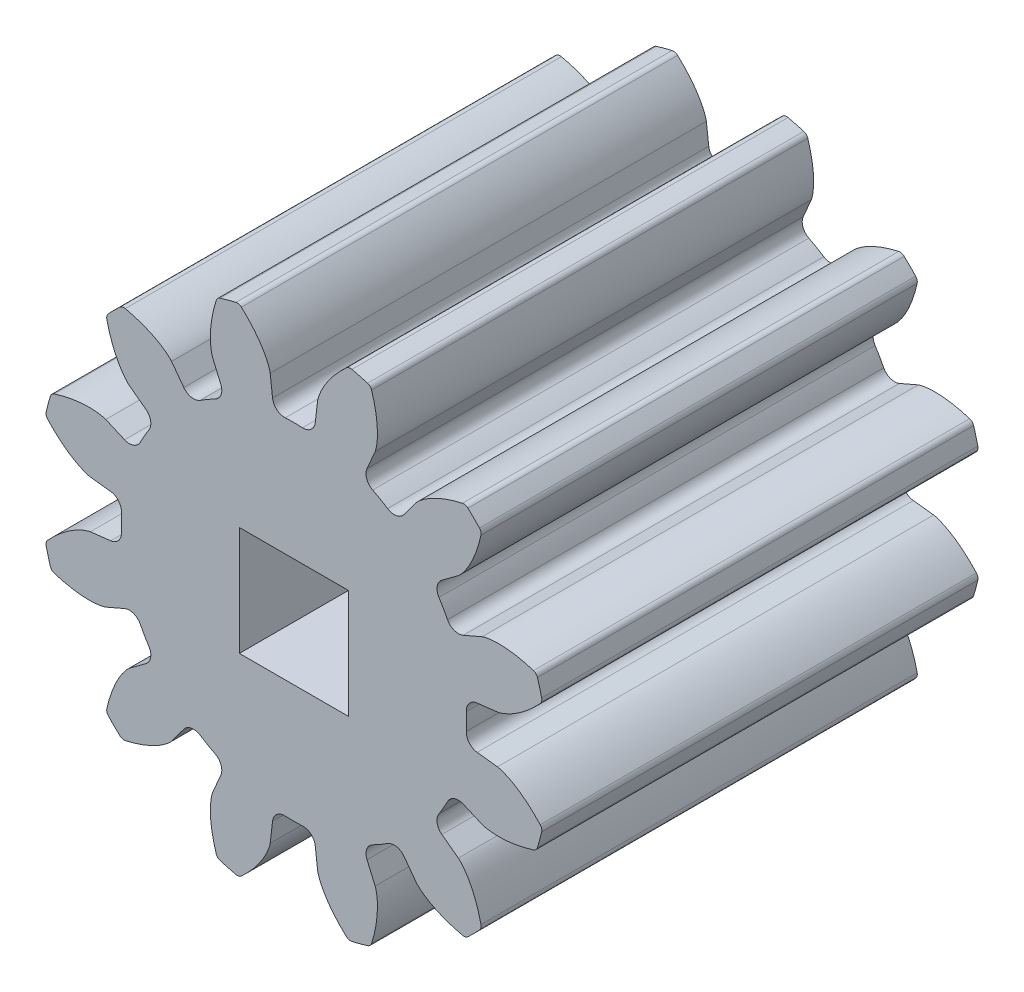
SolidWorks part; units mm, degrees
material "ABS"
ref_plane "Front" through (0, 0, 0) normal (0, 0, 1) x (1, 0, 0)
ref_plane "Top" through (0, 0, 0) normal (0, 1, 0) x (1, 0, 0)
ref_plane "Right" through (0, 0, 0) normal (1, 0, 0) x (0, 0, -1)
sketch "Sketch1" plane through (0, 0, 0) normal (0, 0, 1) x (1, 0, 0)
  circle A0 centre (0, 0) radius 7.4083
extrude "Boss-Extrude1" add sketch "Sketch1" along normal blind 12.7
sketch "Sketch3" plane through (0, 0, 0) normal (0, 0, 1) x (1, 0, 0)
  line L0 (0, 0) -> (43.7181, 0) construction
  line L2 (0, 0) -> (-0.5818, 4.9933) construction
  line L3 (0, 0) -> (0.5818, 4.9933) construction
  line L4 (0.5818, 4.9933) -> (0.6906, 5.927) construction
  line L5 (0, 0) -> (0, 61.276) construction
  line L6 (-0.5818, 4.9933) -> (-0.6906, 5.927) construction
  circle A0 centre (0, 0) radius 7.4083 construction
  circle A1 centre (0, 0) radius 6.35 construction
  circle A2 centre (0, 0) radius 5.967 construction
  arc A3 (0.5818, 4.9933) -> (-0.5818, 4.9933) centre (0, 0) ccw construction
  arc A5 (1.5983, 7.2339) -> (-1.5983, 7.2339) centre (0, 0) ccw
  spline S0 degree 4 poles (-0.6906, 5.927) (-0.6909, 5.9293) (-0.6919, 5.9359) (-0.6942, 5.9484) (-0.6987, 5.9686) (-0.7052, 5.9942) (-0.7148, 6.0271) (-0.7275, 6.0655) (-0.7428, 6.1073) (-0.761, 6.1523) (-0.7804, 6.1969) (-0.8011, 6.2409) (-0.8228, 6.2844) (-0.8503, 6.3367) (-0.8852, 6.3986) (-0.9285, 6.47) (-0.9807, 6.5497) (-1.0371, 6.6294) (-1.0952, 6.7066) (-1.1568, 6.7832) (-1.2185, 6.8562) (-1.2856, 6.9304) (-1.3489, 6.9981) (-1.4232, 7.0721) (-1.484, 7.1312) (-1.5675, 7.2071) (-1.6179, 7.2513) (-1.6779, 7.3023) (-1.7051, 7.3245) (-1.7219, 7.3382) knots 0 0 0 0 0 0.005377 0.015084 0.028532 0.04661 0.064855 0.092111 0.119476 0.146842 0.174209 0.201575 0.228941 0.256307 0.307035 0.361767 0.4165 0.471232 0.525964 0.580697 0.635429 0.690161 0.744894 0.799626 0.854358 0.909091 0.954545 1 1 1 1 1 construction
  spline S1 degree 4 poles (-0.6906, 5.927) (-0.6909, 5.9293) (-0.6919, 5.9359) (-0.6942, 5.9484) (-0.6987, 5.9686) (-0.7052, 5.9942) (-0.7148, 6.0271) (-0.7275, 6.0655) (-0.7428, 6.1073) (-0.761, 6.1523) (-0.7804, 6.1969) (-0.8011, 6.2409) (-0.8228, 6.2844) (-0.8503, 6.3367) (-0.8852, 6.3986) (-0.9285, 6.47) (-0.9807, 6.5497) (-1.0371, 6.6294) (-1.0952, 6.7066) (-1.1568, 6.7832) (-1.2185, 6.8562) (-1.2856, 6.9304) (-1.3489, 6.9981) (-1.4232, 7.0721) (-1.484, 7.1312) (-1.5494, 7.1906) (-1.5816, 7.2193) (-1.5983, 7.2339) knots 0 0 0 0 0 0.005377 0.015084 0.028532 0.04661 0.064855 0.092111 0.119476 0.146842 0.174209 0.201575 0.228941 0.256307 0.307035 0.361767 0.4165 0.471232 0.525964 0.580697 0.635429 0.690161 0.744894 0.799626 0.854358 0.909091 0.909091 0.909091 0.909091 0.909091
  spline S2 degree 4 poles (0.6906, 5.927) (0.6909, 5.9293) (0.6919, 5.9359) (0.6942, 5.9484) (0.6987, 5.9686) (0.7052, 5.9942) (0.7148, 6.0271) (0.7275, 6.0655) (0.7428, 6.1073) (0.761, 6.1523) (0.7804, 6.1969) (0.8011, 6.2409) (0.8228, 6.2844) (0.8503, 6.3367) (0.8852, 6.3986) (0.9285, 6.47) (0.9807, 6.5497) (1.0371, 6.6294) (1.0952, 6.7066) (1.1568, 6.7832) (1.2185, 6.8562) (1.2856, 6.9304) (1.3489, 6.9981) (1.4232, 7.0721) (1.484, 7.1312) (1.5675, 7.2071) (1.6179, 7.2513) (1.6779, 7.3023) (1.7051, 7.3245) (1.7219, 7.3382) knots 0 0 0 0 0 0.005377 0.015084 0.028532 0.04661 0.064855 0.092111 0.119476 0.146842 0.174209 0.201575 0.228941 0.256307 0.307035 0.361767 0.4165 0.471232 0.525964 0.580697 0.635429 0.690161 0.744894 0.799626 0.854358 0.909091 0.954545 1 1 1 1 1 construction
  spline S3 degree 4 poles (0.6906, 5.927) (0.6909, 5.9293) (0.6919, 5.9359) (0.6942, 5.9484) (0.6987, 5.9686) (0.7052, 5.9942) (0.7148, 6.0271) (0.7275, 6.0655) (0.7428, 6.1073) (0.761, 6.1523) (0.7804, 6.1969) (0.8011, 6.2409) (0.8228, 6.2844) (0.8503, 6.3367) (0.8852, 6.3986) (0.9285, 6.47) (0.9807, 6.5497) (1.0371, 6.6294) (1.0952, 6.7066) (1.1568, 6.7832) (1.2185, 6.8562) (1.2856, 6.9304) (1.3489, 6.9981) (1.4232, 7.0721) (1.484, 7.1312) (1.5494, 7.1906) (1.5816, 7.2193) (1.5983, 7.2339) knots 0 0 0 0 0 0.005377 0.015084 0.028532 0.04661 0.064855 0.092111 0.119476 0.146842 0.174209 0.201575 0.228941 0.256307 0.307035 0.361767 0.4165 0.471232 0.525964 0.580697 0.635429 0.690161 0.744894 0.799626 0.854358 0.909091 0.909091 0.909091 0.909091 0.909091
  point P0 (0, 5.0271)
sketch "DCLTBC" plane through (0, 0, 0) normal (0, 0, 1) x (1, 0, 0)
  line L0 (0, 0) -> (41.04, 0) construction
  line L1 (-0.5818, 4.9933) -> (-0.6906, 5.927) construction
  line L2 (0.5818, 4.9933) -> (0.6906, 5.927) construction
  line L3 (-0.5818, 4.9933) -> (-0.6906, 5.927)
  line L4 (0.5818, 4.9933) -> (0.6906, 5.927)
  line L5 (0, 0) -> (0, 104.9356) construction
  circle A0 centre (0, 0) radius 7.4083
  circle A1 centre (0, 0) radius 6.35 construction
  circle A2 centre (0, 0) radius 5.967 construction
  arc A3 (0.5818, 4.9933) -> (-0.5818, 4.9933) centre (0, 0) ccw construction
  arc A4 (0.5818, 4.9933) -> (-0.5818, 4.9933) centre (0, 0) ccw
  spline S0 degree 4 poles (-992.2327, -123.7493) (-11.7184, 3.7577) (-0.7821, 5.3359) (-0.6334, 5.6707) (-0.6987, 5.9686) (-0.7052, 5.9942) (-0.7148, 6.0271) (-0.7275, 6.0655) (-0.7428, 6.1073) (-0.761, 6.1523) (-0.7804, 6.1969) (-0.8011, 6.2409) (-0.8228, 6.2844) (-0.8503, 6.3367) (-0.8852, 6.3986) (-0.9285, 6.47) (-0.9807, 6.5497) (-1.0371, 6.6294) (-1.0952, 6.7066) (-1.1568, 6.7832) (-1.2185, 6.8562) (-1.2856, 6.9304) (-1.3489, 6.9981) (-1.4232, 7.0721) (-1.7629, 7.4024) (-3.091, 8.4823) (16.0015, -8.3782) (-754.2601, 665.5952) knots -0.639841 -0.639841 -0.639841 -0.639841 -0.639841 0.005377 0.015084 0.028532 0.04661 0.064855 0.092111 0.119476 0.146842 0.174209 0.201575 0.228941 0.256307 0.307035 0.361767 0.4165 0.471232 0.525964 0.580697 0.635429 0.690161 0.744894 0.799626 0.854358 1.913215 1.913215 1.913215 1.913215 1.913215 only from (-0.6906, 5.927) to (-1.5983, 7.2339) construction
  spline S1 degree 4 poles (992.2327, -123.7493) (11.7184, 3.7577) (0.7821, 5.3359) (0.6334, 5.6707) (0.6987, 5.9686) (0.7052, 5.9942) (0.7148, 6.0271) (0.7275, 6.0655) (0.7428, 6.1073) (0.761, 6.1523) (0.7804, 6.1969) (0.8011, 6.2409) (0.8228, 6.2844) (0.8503, 6.3367) (0.8852, 6.3986) (0.9285, 6.47) (0.9807, 6.5497) (1.0371, 6.6294) (1.0952, 6.7066) (1.1568, 6.7832) (1.2185, 6.8562) (1.2856, 6.9304) (1.3489, 6.9981) (1.4232, 7.0721) (1.7629, 7.4024) (3.091, 8.4823) (-16.0015, -8.3782) (754.2601, 665.5952) knots -0.639841 -0.639841 -0.639841 -0.639841 -0.639841 0.005377 0.015084 0.028532 0.04661 0.064855 0.092111 0.119476 0.146842 0.174209 0.201575 0.228941 0.256307 0.307035 0.361767 0.4165 0.471232 0.525964 0.580697 0.635429 0.690161 0.744894 0.799626 0.854358 1.913215 1.913215 1.913215 1.913215 1.913215 only from (0.6906, 5.927) to (1.5983, 7.2339) construction
  spline S2 degree 4 poles (-0.6906, 5.927) (-0.6909, 5.9293) (-0.6919, 5.9359) (-0.6942, 5.9484) (-0.6987, 5.9686) (-0.7052, 5.9942) (-0.7148, 6.0271) (-0.7275, 6.0655) (-0.7428, 6.1073) (-0.761, 6.1523) (-0.7804, 6.1969) (-0.8011, 6.2409) (-0.8228, 6.2844) (-0.8503, 6.3367) (-0.8852, 6.3986) (-0.9285, 6.47) (-0.9807, 6.5497) (-1.0371, 6.6294) (-1.0952, 6.7066) (-1.1568, 6.7832) (-1.2185, 6.8562) (-1.2856, 6.9304) (-1.3489, 6.9981) (-1.4232, 7.0721) (-1.484, 7.1312) (-1.5494, 7.1906) (-1.5816, 7.2193) (-1.5983, 7.2339) knots 0 0 0 0 0 0.005377 0.015084 0.028532 0.04661 0.064855 0.092111 0.119476 0.146842 0.174209 0.201575 0.228941 0.256307 0.307035 0.361767 0.4165 0.471232 0.525964 0.580697 0.635429 0.690161 0.744894 0.799626 0.854358 0.909091 0.909091 0.909091 0.909091 0.909091
  spline S3 degree 4 poles (0.6906, 5.927) (0.6909, 5.9293) (0.6919, 5.9359) (0.6942, 5.9484) (0.6987, 5.9686) (0.7052, 5.9942) (0.7148, 6.0271) (0.7275, 6.0655) (0.7428, 6.1073) (0.761, 6.1523) (0.7804, 6.1969) (0.8011, 6.2409) (0.8228, 6.2844) (0.8503, 6.3367) (0.8852, 6.3986) (0.9285, 6.47) (0.9807, 6.5497) (1.0371, 6.6294) (1.0952, 6.7066) (1.1568, 6.7832) (1.2185, 6.8562) (1.2856, 6.9304) (1.3489, 6.9981) (1.4232, 7.0721) (1.484, 7.1312) (1.5494, 7.1906) (1.5816, 7.2193) (1.5983, 7.2339) knots 0 0 0 0 0 0.005377 0.015084 0.028532 0.04661 0.064855 0.092111 0.119476 0.146842 0.174209 0.201575 0.228941 0.256307 0.307035 0.361767 0.4165 0.471232 0.525964 0.580697 0.635429 0.690161 0.744894 0.799626 0.854358 0.909091 0.909091 0.909091 0.909091 0.909091
extrude "Cut-Extrude-DCLTBC" cut sketch "DCLTBC" along normal through all
fillet "Fillet-Tip-DCLTBC" radius 0.1775 2 edges at (1.5983, 7.2339, 6.35) (-1.5983, 7.2339, 6.35)
fillet "Fillet-Root-DCLTBC" radius 0.3551 2 edges at (-0.5818, 4.9933, 6.35) (0.5818, 4.9933, 6.35)
pattern_circular "CirPattern-DCLTBC" count 12 over 360 about axis through (0, 0, 12.7) along (0, 0, 1) of "Cut-Extrude-DCLTBC", "Fillet-Tip-DCLTBC", "Fillet-Root-DCLTBC"
sketch "DCGTBC" [suppressed] plane through (0, 0, 0) normal (0, 0, 1) x (1, 0, 0)
  line L0 (0, 0) -> (41.04, 0) construction
  line L1 (-33.4742, 2.9286) -> (0, 0) construction
  line L2 (0, 0) -> (33.4742, 2.9286) construction
  line L3 (0, 0) -> (-16.5124, 0)
  line L5 (0, 0) -> (0, 104.9356) construction
  circle A0 centre (0, 0) radius 35.9833
  circle A1 centre (0, 0) radius 34.925 construction
  circle A2 centre (0, 0) radius 32.8188 construction
  arc A3 (0.2989, 33.6008) -> (-0.2989, 33.6008) centre (0, 0) ccw construction
  arc A11 (33.4742, 2.9286) -> (-33.4742, 2.9286) centre (0, 0) ccw
  spline S4 degree 4 poles (999.6179, -3.7707) (12.1623, 31.0827) (0.4581, 31.7209) (0.2553, 32.3127) (0.2967, 32.9045) (0.3017, 32.9586) (0.3095, 33.0284) (0.3204, 33.1106) (0.3343, 33.201) (0.3514, 33.2993) (0.3703, 33.3974) (0.3907, 33.4951) (0.4126, 33.5925) (0.4408, 33.7105) (0.477, 33.8518) (0.523, 34.017) (0.5794, 34.2042) (0.6413, 34.395) (0.706, 34.5826) (0.7756, 34.772) (0.846, 34.9552) (0.9235, 35.1454) (0.9973, 35.3209) (1.0848, 35.5175) (1.4313, 36.2799) (2.6636, 38.6565) (-10.9768, 10.7922) (444.1484, 932.5353) knots -0.603811 -0.603811 -0.603811 -0.603811 -0.603811 0.005377 0.015084 0.028532 0.04661 0.064855 0.092111 0.119476 0.146842 0.174209 0.201575 0.228941 0.256307 0.307035 0.361767 0.4165 0.471232 0.525964 0.580697 0.635429 0.690161 0.744894 0.799626 0.854358 1.742885 1.742885 1.742885 1.742885 1.742885 only from (0.2919, 32.8175) to (1.2943, 35.96) construction
  spline S5 degree 4 poles (-999.6179, -3.7707) (-12.1623, 31.0827) (-0.4581, 31.7209) (-0.2553, 32.3127) (-0.2967, 32.9045) (-0.3017, 32.9586) (-0.3095, 33.0284) (-0.3204, 33.1106) (-0.3343, 33.201) (-0.3514, 33.2993) (-0.3703, 33.3974) (-0.3907, 33.4951) (-0.4126, 33.5925) (-0.4408, 33.7105) (-0.477, 33.8518) (-0.523, 34.017) (-0.5794, 34.2042) (-0.6413, 34.395) (-0.706, 34.5826) (-0.7756, 34.772) (-0.846, 34.9552) (-0.9235, 35.1454) (-0.9973, 35.3209) (-1.0848, 35.5175) (-1.4313, 36.2799) (-2.6636, 38.6565) (10.9768, 10.7922) (-444.1484, 932.5353) knots -0.603811 -0.603811 -0.603811 -0.603811 -0.603811 0.005377 0.015084 0.028532 0.04661 0.064855 0.092111 0.119476 0.146842 0.174209 0.201575 0.228941 0.256307 0.307035 0.361767 0.4165 0.471232 0.525964 0.580697 0.635429 0.690161 0.744894 0.799626 0.854358 1.742885 1.742885 1.742885 1.742885 1.742885 only from (-0.2919, 32.8175) to (-1.2943, 35.96) construction
  spline S6 degree 4 poles (0.2919, 32.8175) (0.292, 32.8224) (0.2924, 32.8361) (0.2937, 32.8621) (0.2967, 32.9045) (0.3017, 32.9586) (0.3095, 33.0284) (0.3204, 33.1106) (0.3343, 33.201) (0.3514, 33.2993) (0.3703, 33.3974) (0.3907, 33.4951) (0.4126, 33.5925) (0.4408, 33.7105) (0.477, 33.8518) (0.523, 34.017) (0.5794, 34.2042) (0.6413, 34.395) (0.706, 34.5826) (0.7756, 34.772) (0.846, 34.9552) (0.9235, 35.1454) (0.9973, 35.3209) (1.0848, 35.5175) (1.1568, 35.676) (1.2354, 35.8397) (1.2742, 35.9193) (1.2943, 35.96) knots 0 0 0 0 0 0.005377 0.015084 0.028532 0.04661 0.064855 0.092111 0.119476 0.146842 0.174209 0.201575 0.228941 0.256307 0.307035 0.361767 0.4165 0.471232 0.525964 0.580697 0.635429 0.690161 0.744894 0.799626 0.854358 0.909091 0.909091 0.909091 0.909091 0.909091
  spline S7 degree 4 poles (-0.2919, 32.8175) (-0.292, 32.8224) (-0.2924, 32.8361) (-0.2937, 32.8621) (-0.2967, 32.9045) (-0.3017, 32.9586) (-0.3095, 33.0284) (-0.3204, 33.1106) (-0.3343, 33.201) (-0.3514, 33.2993) (-0.3703, 33.3974) (-0.3907, 33.4951) (-0.4126, 33.5925) (-0.4408, 33.7105) (-0.477, 33.8518) (-0.523, 34.017) (-0.5794, 34.2042) (-0.6413, 34.395) (-0.706, 34.5826) (-0.7756, 34.772) (-0.846, 34.9552) (-0.9235, 35.1454) (-0.9973, 35.3209) (-1.0848, 35.5175) (-1.1568, 35.676) (-1.2354, 35.8397) (-1.2742, 35.9193) (-1.2943, 35.96) knots 0 0 0 0 0 0.005377 0.015084 0.028532 0.04661 0.064855 0.092111 0.119476 0.146842 0.174209 0.201575 0.228941 0.256307 0.307035 0.361767 0.4165 0.471232 0.525964 0.580697 0.635429 0.690161 0.744894 0.799626 0.854358 0.909091 0.909091 0.909091 0.909091 0.909091
  dimension "D1" = 5
  dimension "D2" = 5
extrude "Cut-Extrude-DCGTBC" [suppressed] cut sketch "DCGTBC" along normal through all
fillet "Fillet-Tip-DCGTBC" [suppressed] radius 0.1775
pattern_circular "CirPattern-DCGTBC" [suppressed] count 12 over 360
sketch "Sketch4" plane through (0, 0, 12.7) normal (0, 0, 1) x (1, 0, 0)
  line L1 (-1.5875, -1.5875) -> (1.5875, -1.5875)
  line L2 (-1.5875, -1.5875) -> (-1.5875, 1.5875)
  line L3 (-1.5875, 1.5875) -> (1.5875, 1.5875)
  line L4 (1.5875, -1.5875) -> (1.5875, 1.5875)
  line L5 (-1.5875, -1.5875) -> (1.5875, 1.5875) construction
  line L6 (-1.5875, 1.5875) -> (1.5875, -1.5875) construction
  point P0 (0, 0)
  dimension "D1" = 3.175
extrude "Cut-Extrude2" cut sketch "Sketch4" against normal through all
equation "\"DiametralPitch\"= 24'Diametral Pitch"
equation "\"NumTeeth\"= 12'Number of Teeth"
equation "\"PressureAngle\"= 20deg'Pressure Angle"
equation "\"Addendum\"= 1 / \"DiametralPitch\"'Addendum"
equation "\"Dedendum\"= 1.25 / \"DiametralPitch\"'Dedendum"
equation "\"WorkingDepth\"= 2 / \"DiametralPitch\"'Working Depth - here for REF (Not used in building model)"
equation "\"WholeDepth\"= 2.25 / \"DiametralPitch\"'Whole Depth - here for REF (Not used in building model)"
equation "\"Clearance\"= .25 / \"DiametralPitch\"'Clearance"
equation "\"CircularPitch\"= pi / \"DiametralPitch\"'Circular Pitch - here for REF (Not used in building model)"
equation "\"PitchCircle\"= \"NumTeeth\" / \"DiametralPitch\"'Pitch Circle - or - Pitch Diameter"
equation "\"OutsideDiameter\"= ( \"NumTeeth\" + 2 ) / \"DiametralPitch\"'Outside Diameter"
equation "\"Fillet_Root\"= \"Clearance\" * cos ( \"PressureAngle\" ) * tan ( ( 90 + \"PressureAngle\" ) / 2 ) 'Fillet Root"
equation "\"AddendumCircle\"= \"PitchCircle\" + ( 2 * \"Addendum\" )'Addendum Circle - or - Addendum Diameter"
equation "\"DedendumCircle\"= \"PitchCircle\" - ( 2 * \"Dedendum\" )'Dedendum Circle - or - Dedendum Diameter"
equation "\"BaseCircle\"= \"PitchCircle\" * cos ( \"PressureAngle\" )'Base Circle - Base Diameter"
equation "\"PitchAngle\"= 360deg / \"NumTeeth\"'Pitch Angle"
equation "\"Alpha\"= sqr ( \"PitchCircle\" ^ 2 - \"BaseCircle\" ^ 2 ) / \"BaseCircle\" * 180 / PI - \"PressureAngle\"'Alpha - Used for Calculating Beta"
equation "\"Beta\"= ( \"PitchAngle\" / 4 - ( \"Alpha\" - 90 ) )'Beta - Used in definition of the parameters for the parametric equation driven curve"
equation "\"Gamma\"= ( \"PitchAngle\" / 4 - ( \"Alpha\" + 90 ) )'Gamma - Used in definition of the parameters for the parametric equation driven curve"
equation "\"Phi\"= sqr ( ( \"AddendumCircle\" / 2 ) ^ 2 - ( \"BaseCircle\" / 2 ) ^ 2 ) / ( \"BaseCircle\" / 2 )'Phi - Used in definition of the parameters for the parametric equation driven curve"
equation "\"DCGTBC\"= iif ( \"DedendumCircle\" > \"BaseCircle\" , \"unsuppressed\" , \"suppressed\" )'if Dedendum Circle IS GREATER THAN BaseCircle THEN UnsuppressORSuppress FEATURE"
equation "\"DCLTBC\"= iif ( \"DedendumCircle\" - .002 > \"BaseCircle\" , \"suppressed\" , \"unsuppressed\" )'if Dedendum Circle - .002 IS GREATER THAN BaseCircle THEN SuppressORUnsuppress FEATURE"
equation "\"Cut-Extrude-DCGTBC\"= iif ( \"DedendumCircle\" > \"BaseCircle\" , \"unsuppressed\" , \"suppressed\" )'if Dedendum Circle IS GREATER THAN BaseCircle THEN UnsuppressORSuppress FEATURE"
equation "\"Cut-Extrude-DCLTBC\"= iif ( \"DedendumCircle\" - .002 > \"BaseCircle\" , \"suppressed\" , \"unsuppressed\" )'if Dedendum Circle - .002 IS GREATER THAN BaseCircle THEN SuppressORUnsuppress FEATURE"
equation "\"CirPattern-DCGTBC\"= iif ( \"DedendumCircle\" > \"BaseCircle\" , \"unsuppressed\" , \"suppressed\" )'if Dedendum Circle IS GREATER THAN BaseCircle THEN UnsuppressORSuppress FEATURE"
equation "\"CirPattern-DCLTBC\"= iif ( \"DedendumCircle\" - .002 > \"BaseCircle\" , \"suppressed\" , \"unsuppressed\" )'if Dedendum Circle - .002 IS GREATER THAN BaseCircle THEN SuppressORUnsuppress FEATURE"
equation "\"Fillet-Tip-DCGTBC\"= iif ( \"DedendumCircle\" > \"BaseCircle\" , \"unsuppressed\" , \"suppressed\" )'if Dedendum Circle IS GREATER THAN BaseCircle THEN UnsuppressORSuppress FEATURE"
equation "\"Fillet-Tip-DCLTBC\"= iif ( \"DedendumCircle\" - .002 > \"BaseCircle\" , \"suppressed\" , \"unsuppressed\" )'if Dedendum Circle - .002 IS GREATER THAN BaseCircle THEN SuppressORUnsuppress FEATURE"
equation "\"Fillet-Root-DCLTBC\"= iif ( \"DedendumCircle\" - .002 > \"BaseCircle\" , \"suppressed\" , \"unsuppressed\" )'if Dedendum Circle - .002 IS GREATER THAN BaseCircle THEN SuppressORUnsuppress FEATURE"
equation "\"D1@CirPattern-DCGTBC\"= \"NumTeeth\"'Number of Teeth"
equation "\"D1@CirPattern-DCLTBC\"= \"NumTeeth\"'Number of Teeth"
equation "\"D1@Fillet-Tip-DCGTBC\"= \"Fillet_Root\" / 2 'Tip Rad For Large No of Teeth"
equation "\"D1@Fillet-Tip-DCLTBC\"=\"Fillet_Root\" / 2'Tip Rad For Small No of Teeth"
equation "\"D1@Fillet-Root-DCLTBC\"= \"Fillet_Root\"'Fillet Root"
